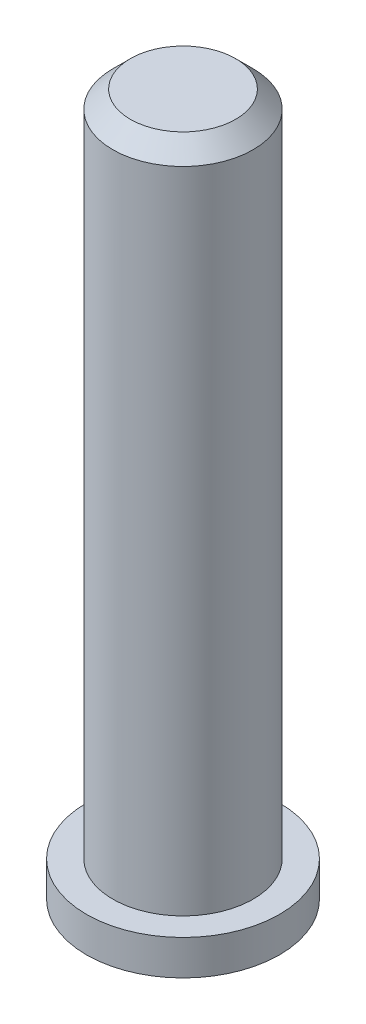
SolidWorks part; units mm, degrees
ref_plane "Спереди" through (0, 0, 0) normal (0, 0, 1) x (1, 0, 0)
ref_plane "Сверху" through (0, 0, 0) normal (0, 1, 0) x (1, 0, 0)
ref_plane "Справа" through (0, 0, 0) normal (1, 0, 0) x (0, 0, -1)
sketch "Эскиз1" plane through (0, 0, 0) normal (0, 1, 0) x (1, 0, 0)
  circle A0 centre (0, 0) radius 2
  dimension "D1" = 4
extrude "Вытянуть1" add sketch "Эскиз1" along normal blind 20
chamfer "Фаска1" distance 0.5 angle 45 1 edges at (0, 20, 2)
sketch "Эскиз2" plane through (0, 0, 0) normal (0, -1, 0) x (1, 0, 0)
  circle A0 centre (0, 0) radius 2.75
  dimension "D1" = 5.5
extrude "Вытянуть2" add sketch "Эскиз2" against normal blind 1
sketch "Эскиз3" plane through (0, 0, 0) normal (0, -1, 0) x (1, 0, 0)
  circle A0 centre (0, 0) radius 0.325
  dimension "D1" = 0.65
extrude "Вытянуть3" add sketch "Эскиз3" along normal blind 0.55
